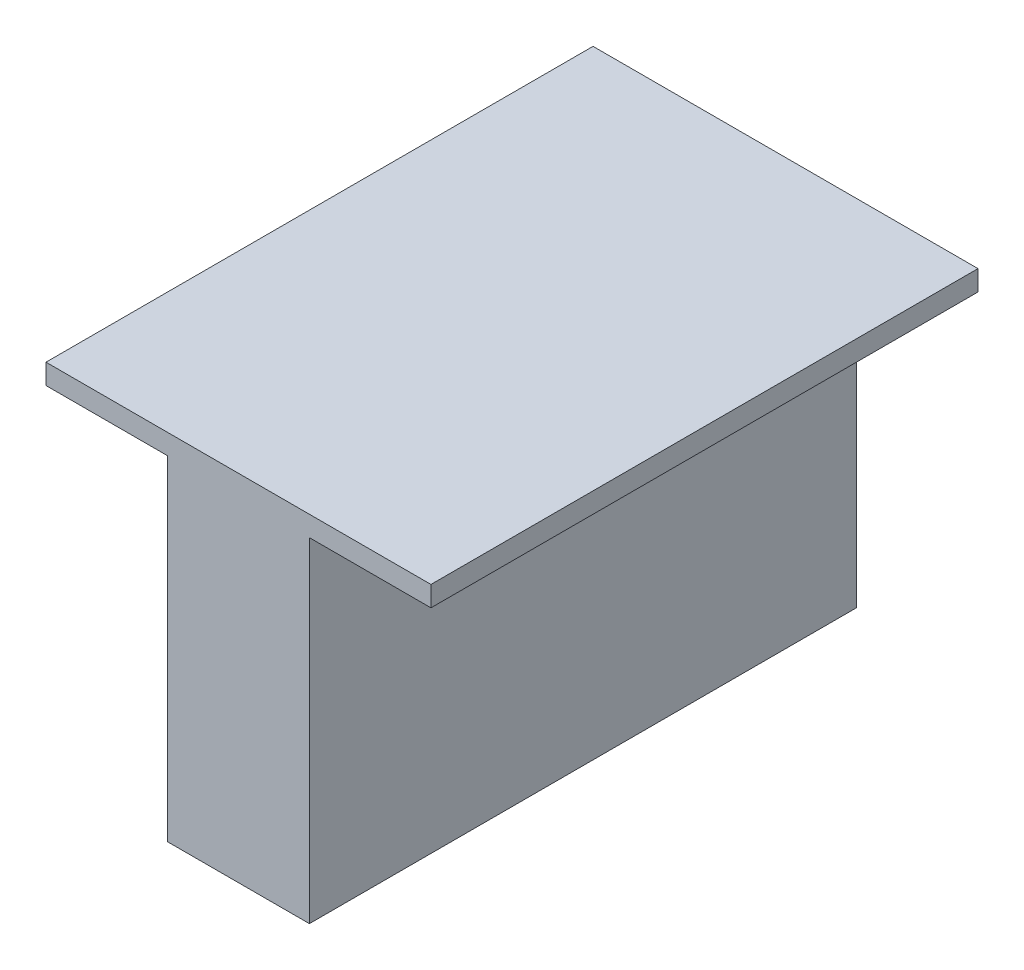
SolidWorks part; units mm, degrees
ref_plane "Front Plane" through (0, 0, 0) normal (0, 0, 1) x (1, 0, 0)
ref_plane "Top Plane" through (0, 0, 0) normal (0, 1, 0) x (1, 0, 0)
ref_plane "Right Plane" through (0, 0, 0) normal (1, 0, 0) x (0, 0, -1)
sketch "Sketch1" plane through (0, 0, 0) normal (0, 1, 0) x (1, 0, 0)
  line L1 (0, 0) -> (14, 0)
  line L2 (0, 0) -> (0, 54)
  line L3 (0, 54) -> (14, 54)
  line L4 (14, 0) -> (14, 54)
extrude "Boss-Extrude2" add sketch "Sketch1" along normal blind 35
shell "Shell2" thickness 5
sketch "Sketch2" plane through (0, 0, 0) normal (-1, 0, 0) x (0, 0, 1)
  line L0 (-54, 35) -> (-54, 33)
  line L1 (-54, 35) -> (-54, 0) construction
  line L2 (-54, 33) -> (0, 33)
  line L3 (0, 35) -> (0, 0) construction
  line L4 (0, 33) -> (0, 35)
  line L5 (0, 35) -> (-54, 35)
extrude "Boss-Extrude3" add sketch "Sketch2" along normal blind 12
sketch "Sketch3" plane through (14, 0, 0) normal (1, 0, 0) x (0, 0, -1)
  line L0 (0, 35) -> (0, 33)
  line L1 (0, 35) -> (0, 0) construction
  line L2 (0, 33) -> (54, 33)
  line L3 (54, 35) -> (54, 0) construction
  line L4 (54, 33) -> (54, 35)
  line L5 (54, 35) -> (0, 35)
extrude "Boss-Extrude4" add sketch "Sketch3" along normal blind 12
